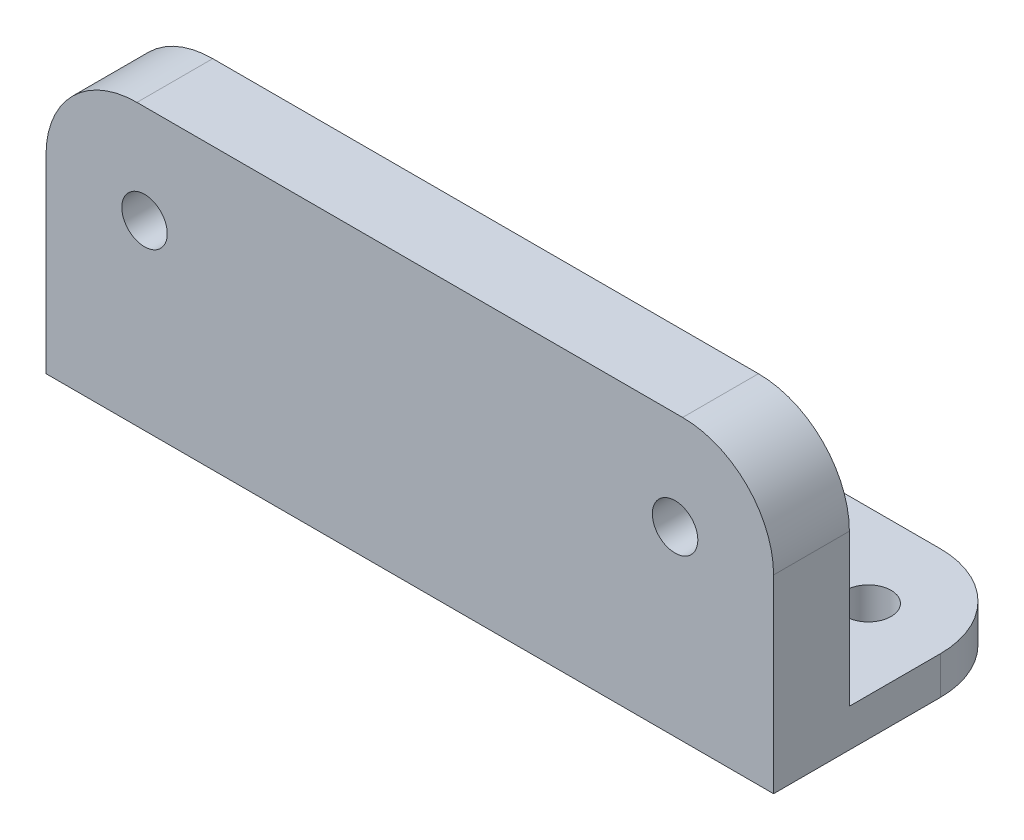
SolidWorks part; units mm, degrees
ref_plane "前视基准面" through (0, 0, 0) normal (0, 0, 1) x (1, 0, 0)
ref_plane "上视基准面" through (0, 0, 0) normal (0, 1, 0) x (1, 0, 0)
ref_plane "右视基准面" through (0, 0, 0) normal (1, 0, 0) x (0, 0, -1)
sketch "草图1" plane through (0, 0, 0) normal (0, 1, 0) x (1, 0, 0)
  line L1 (-24, 8.5) -> (24, 8.5)
  line L2 (-24, 8.5) -> (-24, -8.5)
  line L3 (-24, -8.5) -> (24, -8.5)
  line L4 (24, 8.5) -> (24, -8.5)
  line L5 (-24, 8.5) -> (24, -8.5) construction
  line L6 (-24, -8.5) -> (24, 8.5) construction
  point P0 (0, 0)
extrude "凸台-拉伸1" add sketch "草图1" along normal blind 2.5
sketch "草图2" plane through (0, 2.5, 0) normal (0, 1, 0) x (1, 0, 0)
  line L0 (24, -8.5) -> (24, 8.5) construction
  line L1 (-24, -8.5) -> (24, -8.5)
  line L2 (-24, -8.5) -> (-24, -3.5)
  line L3 (-24, -3.5) -> (24, -3.5)
  line L4 (24, -8.5) -> (24, -3.5)
  dimension "D1" = 5
extrude "凸台-拉伸2" add sketch "草图2" along normal blind 16
sketch "草图3" plane through (0, 2.5, 0) normal (0, 1, 0) x (1, 0, 0)
  line L0 (0, 8.5) -> (0, -3.5) construction
  line L1 (24, 8.5) -> (-24, 8.5) construction
  line L2 (24, -3.5) -> (-24, -3.5) construction
  circle A0 centre (18.75, 3) radius 1.5
  circle A1 centre (-18.75, 3) radius 1.5
  dimension "D1" = 6.5
  dimension "D2" = 37.5
extrude "切除-拉伸1" cut sketch "草图3" against normal blind 20
fillet "圆角1" radius 6 4 edges at (24, 18.5, 6) (-24, 18.5, 6) (-24, 1.25, -8.5) (24, 1.25, -8.5)
sketch "草图4" plane through (0, 0, 3.5) normal (0, 0, -1) x (-1, 0, 0)
  line L0 (0, 18.5) -> (0, 2.5) construction
  line L1 (-18, 18.5) -> (18, 18.5) construction
  line L2 (-24, 2.5) -> (24, 2.5) construction
  circle A0 centre (17.5, 12) radius 1.5
  circle A1 centre (-17.5, 12) radius 1.5
  dimension "D1" = 6.5
  dimension "D2" = 35
extrude "切除-拉伸2" cut sketch "草图4" against normal blind 20
